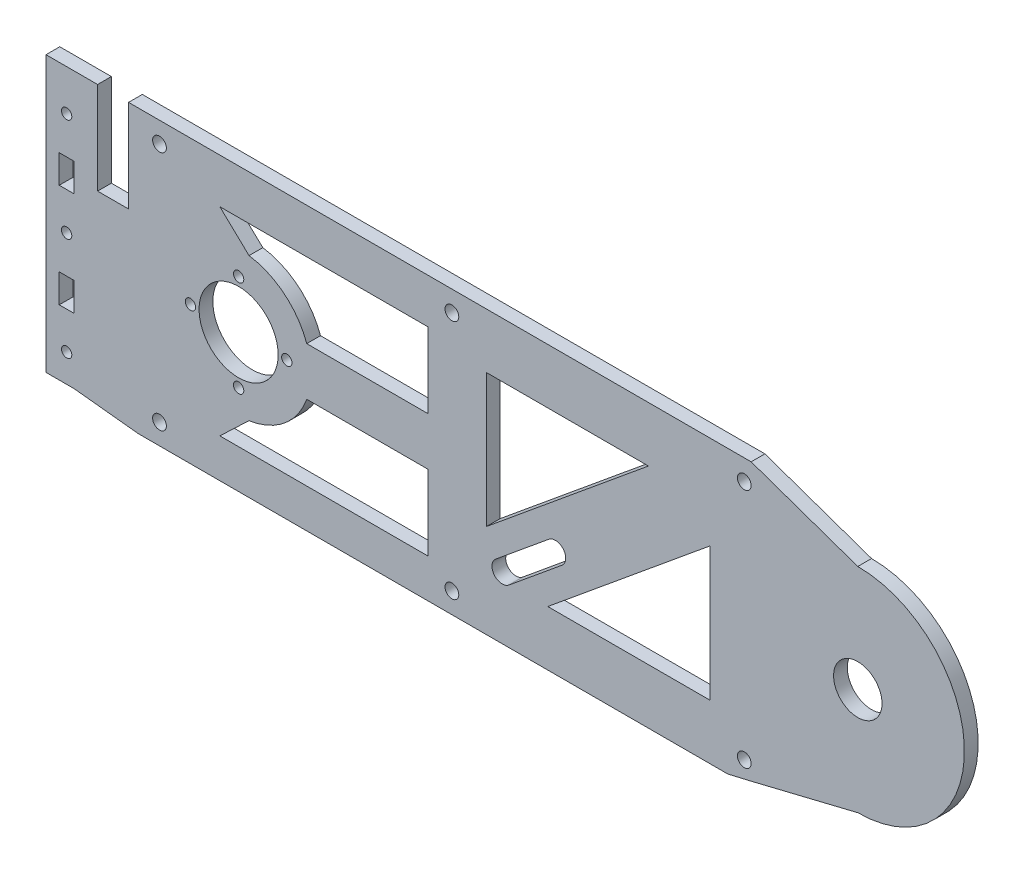
SolidWorks part; units mm, degrees
ref_plane "前视基准面" through (0, 0, 0) normal (0, 0, 1) x (1, 0, 0)
ref_plane "上视基准面" through (0, 0, 0) normal (0, 1, 0) x (1, 0, 0)
ref_plane "右视基准面" through (0, 0, 0) normal (1, 0, 0) x (0, 0, -1)
sketch "草图1" plane through (0, 0, 0) normal (0, 0, 1) x (1, 0, 0)
  line L0 (0.5429, 31.4043) -> (0.5429, 28.4043)
  line L1 (0.5429, 18.9043) -> (0.5429, 10.9043) construction
  line L2 (-1.6071, 10.8043) -> (2.6929, 10.8043)
  line L3 (-1.6071, 10.8043) -> (-1.6071, 19.0043)
  line L4 (-1.6071, 19.0043) -> (2.6929, 19.0043)
  line L5 (2.6929, 10.8043) -> (2.6929, 19.0043)
  line L6 (-1.6071, 10.8043) -> (2.6929, 19.0043) construction
  line L7 (-1.6071, 19.0043) -> (2.6929, 10.8043) construction
  line L8 (2.6929, -19.2957) -> (2.6929, -10.9957)
  line L9 (-1.6071, -19.2957) -> (2.6929, -19.2957)
  line L10 (-1.6071, -19.2957) -> (-1.6071, -10.9957)
  line L11 (-1.6071, -10.9957) -> (2.6929, -10.9957)
  line L12 (0.5429, -0.0957) -> (-5.4571, -0.0957) construction
  line L13 (-5.4571, -0.0957) -> (-5.4571, 41.7543)
  line L14 (-5.4571, 41.7543) -> (261.5429, 41.7543) construction
  line L15 (261.5429, 41.7543) -> (261.5429, -38.2457) construction
  line L17 (-5.4571, -38.2457) -> (-5.4571, -0.0957)
  line L18 (50.5429, -0.0957) -> (96.7433, -0.0957) construction
  line L19 (50.5429, -0.0957) -> (230.5429, -0.0957) construction
  line L21 (199.5429, -0.0957) -> (199.5429, 41.7543) construction
  line L23 (199.5429, 41.7543) -> (230.5429, 30.9043)
  line L26 (230.5429, -31.0957) -> (199.5561, -38.6559)
  line L28 (-5.4571, 41.7543) -> (9.5429, 41.7543)
  line L29 (0.5429, -0.0957) -> (36.5429, -0.0957) construction
  line L32 (21.3658, -40.2457) -> (192.7469, -40.2457)
  line L38 (-5.4571, -38.2457) -> (2.6929, -38.2457)
  line L42 (18.5429, 14.9043) -> (18.5429, 41.7543)
  line L43 (18.5429, 41.7543) -> (199.5429, 41.7543)
  line L44 (9.5429, 41.7543) -> (9.5429, 14.9043)
  line L45 (9.5429, 14.9043) -> (18.5429, 14.9043)
  line L46 (2.6929, -38.2457) -> (21.3658, -40.2457)
  line L47 (192.7469, -40.2457) -> (199.5561, -38.6559)
  circle A0 centre (0.5429, 29.9043) radius 1.5
  circle A1 centre (0.5429, -0.0957) radius 1.5
  circle A2 centre (0.5429, -30.0957) radius 1.5
  circle A3 centre (50.5429, -0.0957) radius 11.5
  circle A4 centre (50.5429, -0.0957) radius 14 construction
  circle A5 centre (50.5429, -14.0957) radius 1.5
  circle A12 centre (36.5429, -0.0957) radius 1.5
  circle A13 centre (50.5429, 13.9043) radius 1.5
  circle A14 centre (64.5429, -0.0957) radius 1.5
  circle A15 centre (230.5429, -0.0957) radius 7.04
  circle A16 centre (230.5429, -0.0957) radius 31 construction
  arc A17 (230.5429, 30.9043) -> (230.5429, -31.0957) centre (230.5429, -0.0957) cw
  point P6 (0.5429, 14.9043)
  dimension "D3" = 23
  dimension "D4" = 4
  dimension "D10" = 38.15
  dimension "D13" = 14.08
  dimension "D1" = 8.2
  dimension "D2" = 4.3
  dimension "D5" = 50
  dimension "D6" = 6
  dimension "D7" = 15
  dimension "D8" = 60
  dimension "D9" = 30
  dimension "D11" = 41.85
  dimension "D12" = 31
  dimension "D14" = 180
  dimension "D15" = 2
  dimension "D17" = 15
extrude "凸台-拉伸1" add sketch "草图1" along normal blind 4
sketch "草图2" plane through (0, 0, 4) normal (0, 0, 1) x (1, 0, 0)
  line L0 (112.5429, -34.2457) -> (197.5429, 35.7543) construction
  line L1 (197.5429, 35.7543) -> (197.5429, -34.2457) construction
  line L2 (197.5429, -34.2457) -> (112.5429, -34.2457) construction
  line L3 (187.5429, -24.2457) -> (140.4162, -24.2457)
  line L4 (140.4162, -24.2457) -> (187.5429, 14.5645)
  line L5 (187.5429, 14.5645) -> (187.5429, -24.2457)
  line L6 (112.5429, -34.2457) -> (112.5429, 35.7543) construction
  line L7 (112.5429, 35.7543) -> (197.5429, 35.7543) construction
  line L8 (122.5429, 25.7543) -> (169.6695, 25.7543)
  line L9 (122.5429, -13.0559) -> (169.6695, 25.7543)
  line L10 (122.5429, -13.0559) -> (122.5429, 25.7543)
  line L11 (27.5429, 35.7543) -> (50.5429, 13.9043) construction
  line L13 (64.5429, -0.0957) -> (112.5429, -0.0957) construction
  line L18 (18.5429, 41.7543) -> (199.5429, 41.7543) construction
  line L19 (18.5429, 14.9043) -> (18.5429, 41.7543) construction
  line L20 (127.1861, -22.1866) -> (142.6247, -9.4724) construction
  line L23 (27.5429, 35.7543) -> (112.5429, 35.7543) construction
  line L24 (112.5429, -0.0957) -> (112.5429, 35.7543) construction
  line L25 (70.3418, 6.9043) -> (105.5429, 6.9043)
  line L26 (105.5429, 6.9043) -> (105.5429, 28.7543)
  line L27 (45.0746, 28.7543) -> (105.5429, 28.7543)
  line L28 (45.0746, 28.7543) -> (53.5684, 20.6852)
  line L29 (105.5429, -7.0957) -> (105.5429, -28.9457)
  line L30 (70.3418, -7.0957) -> (105.5429, -7.0957)
  line L31 (45.0746, -28.9457) -> (53.5684, -20.8766)
  line L32 (45.0746, -28.9457) -> (105.5429, -28.9457)
  line L38 (125.279, -19.8708) -> (140.7176, -7.1566)
  line L39 (129.0932, -24.5023) -> (144.5319, -11.7882)
  line L40 (112.5429, -34.2457) -> (27.5429, -34.2457) construction
  circle A0 centre (27.5429, 35.7543) radius 2
  circle A1 centre (112.5429, 35.7543) radius 2
  circle A2 centre (197.5429, 35.7543) radius 2
  circle A3 centre (112.5429, -34.2457) radius 2
  circle A4 centre (197.5429, -34.2457) radius 2
  circle A5 centre (27.5429, -34.2457) radius 2
  arc A8 (50.5429, 13.9043) -> (64.5429, -0.0957) centre (50.5429, -0.0957) cw construction
  arc A9 (53.5684, 20.6852) -> (70.3418, 6.9043) centre (50.5429, -0.0957) cw
  arc A10 (53.5684, -20.8766) -> (70.3418, -7.0957) centre (50.5429, -0.0957) ccw
  arc A11 (125.279, -19.8708) -> (129.0932, -24.5023) centre (127.1861, -22.1866) ccw
  arc A12 (144.5319, -11.7882) -> (140.7176, -7.1566) centre (142.6247, -9.4724) ccw
  point P24 (27.5429, 35.7543)
  point P31 (134.9054, -15.8295)
  dimension "D3" = 7
  dimension "D4" = 9
  dimension "D1" = 6
  dimension "D2" = 9
  dimension "D5" = 85
  dimension "D6" = 85
  dimension "D7" = 70
extrude "切除-拉伸1" cut sketch "草图2" against normal blind 4
